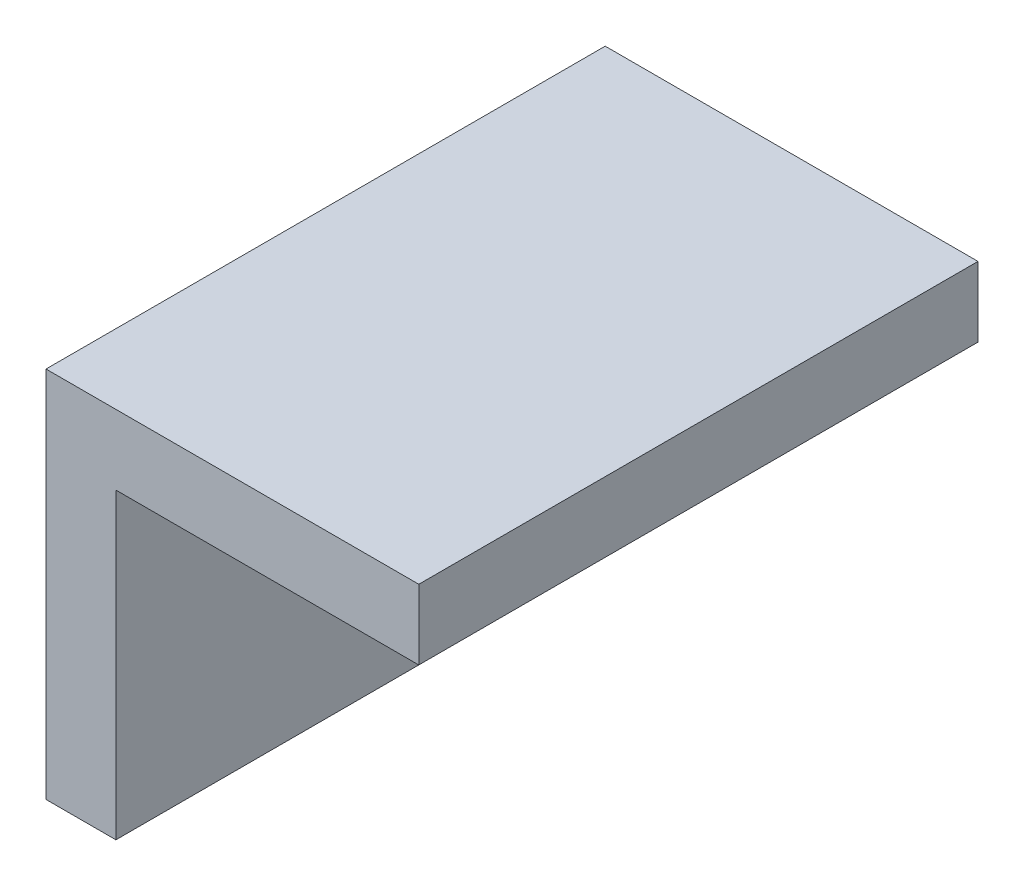
SolidWorks part; units mm, degrees
ref_plane "Alzado" through (0, 0, 0) normal (0, 0, 1) x (1, 0, 0)
ref_plane "Planta" through (0, 0, 0) normal (0, 1, 0) x (1, 0, 0)
ref_plane "Vista lateral" through (0, 0, 0) normal (1, 0, 0) x (0, 0, -1)
sketch "Croquis1" plane through (0, 0, 0) normal (0, 0, 1) x (1, 0, 0)
  line L0 (0, 0) -> (0, -50.8)
  line L1 (0, 0) -> (50.8, 0)
  line L2 (9.525, -9.525) -> (9.525, -50.8)
  line L3 (9.525, -9.525) -> (50.8, -9.525)
  line L4 (50.8, -9.525) -> (50.8, 0)
  line L5 (9.525, -50.8) -> (0, -50.8)
  dimension "D1" = 50.8
  dimension "D2" = 50.8
  dimension "D3" = 9.525
extrude "Saliente-Extruir1" add sketch "Croquis1" along normal blind 76.2
